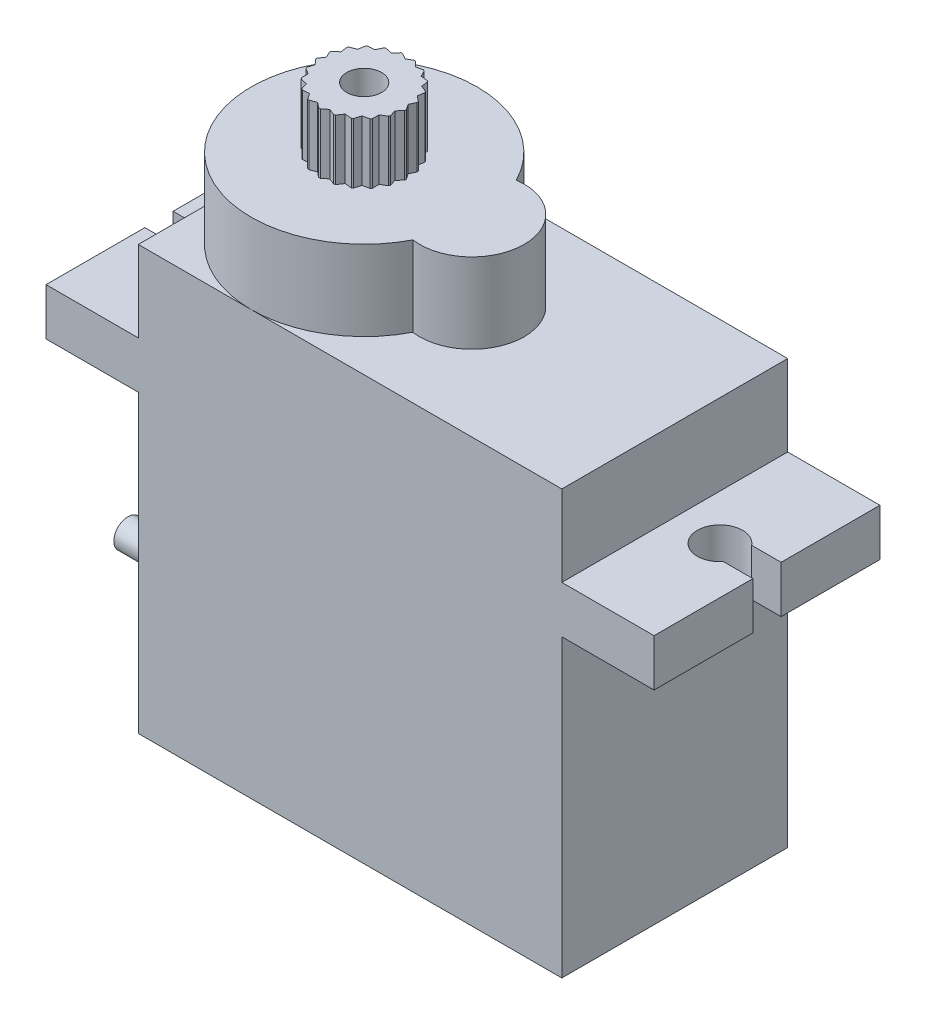
SolidWorks part; units mm, degrees
ref_plane "Front Plane" through (0, 0, 0) normal (0, 0, 1) x (1, 0, 0)
ref_plane "Top Plane" through (0, 0, 0) normal (0, 1, 0) x (1, 0, 0)
ref_plane "Right Plane" through (0, 0, 0) normal (1, 0, 0) x (0, 0, -1)
sketch "Sketch1" plane through (0, 0, 0) normal (0, 1, 0) x (1, 0, 0)
  line L1 (-11.25, -6) -> (11.25, -6)
  line L2 (-11.25, -6) -> (-11.25, 6)
  line L3 (-11.25, 6) -> (11.25, 6)
  line L4 (11.25, -6) -> (11.25, 6)
  line L5 (-11.25, -6) -> (11.25, 6) construction
  line L6 (-11.25, 6) -> (11.25, -6) construction
  point P0 (0, 0)
  dimension "D1" = 22.5
  dimension "D2" = 12
extrude "Boss-Extrude1" add sketch "Sketch1" along normal mid plane 22.5
sketch "Sketch3" plane through (0, 11.25, 0) normal (0, 1, 0) x (1, 0, 0)
  line L0 (-12.375, 0) -> (12.375, 0) construction
  line L1 (11.25, 6) -> (-11.25, 6) construction
  line L2 (-11.25, 6) -> (-11.25, -6) construction
  circle A0 centre (-5.25, 0) radius 6
  circle A1 centre (0.4725, 0) radius 2.7775
  point P10 (3.25, 0)
  point P11 (0.0827, -2.75)
  point P13 (0.0827, 2.75)
  dimension "D1" = 5.5
  dimension "D2" = 14.5
extrude "Boss-Extrude3" add sketch "Sketch3" along normal blind 4.25 contours A0 A1 | A0 A1 | A1 A0
ref_plane "Plane1" through (0, 6.95, 0) normal (0, 1, 0) x (1, 0, 0)
sketch "Sketch4" plane through (0, 6.95, 0) normal (0, 1, 0) x (1, 0, 0)
  line L0 (-5.25, -6) -> (11.25, -6) construction
  line L1 (11.25, 6) -> (16.15, 6)
  line L2 (11.25, 6) -> (11.25, -6)
  line L3 (11.25, -6) -> (16.15, -6)
  line L4 (16.15, 6) -> (16.15, -6)
  dimension "D1" = 4.9
extrude "Boss-Extrude4" add sketch "Sketch4" against normal blind 2.5
sketch "Sketch5" plane through (0, 6.95, 0) normal (0, 1, 0) x (1, 0, 0)
  line L0 (16.15, -6) -> (16.15, 6) construction
  line L1 (16.15, 0.75) -> (14.5867, 0.75)
  line L2 (16.15, -0.75) -> (14.5867, -0.75)
  line L3 (16.15, 0.75) -> (16.15, -0.75)
  line L4 (16.15, 0.75) -> (16.15, -0.75)
  circle A0 centre (13.65, 0) radius 1.2
  point P8 (16.15, 0)
  point P9 (16.15, 0)
  line M7 (16.15, -6) -> (16.15, 6)
  dimension "D2" = 2.4
  dimension "D1" = 2.5
  dimension "D3" = 1.5
extrude "Cut-Extrude1" cut sketch "Sketch5" against normal up to surface (2.5 mm away) contours A0 L2 L1 M7 | A0 up to face at (13.7, 4.45, 0)
mirror "Mirror1" about plane through (0, 0, 0) normal (1, 0, 0) of "Cut-Extrude1", "Boss-Extrude4"
sketch "Sketch6" plane through (-11.25, 0, 0) normal (-1, 0, 0) x (0, 0, 1)
  line L0 (-6, -11.25) -> (6, -11.25) construction
  circle A0 centre (0, -6.75) radius 0.75
  circle A1 centre (1.55, -6.75) radius 0.75
  circle A2 centre (-1.55, -6.75) radius 0.75
  dimension "D1" = 1.5
  dimension "D2" = 1.5
  dimension "D3" = 1.5
  dimension "D4" = 1.55
  dimension "D5" = 1.55
  dimension "D6" = 4.5
extrude "Boss-Extrude5" add sketch "Sketch6" along normal blind 5
sketch "Sketch7" plane through (0, 15.5, 0) normal (0, 1, 0) x (1, 0, 0)
  circle A0 centre (-5.25, 0) radius 2.375
  dimension "D1" = 4.75
extrude "Boss-Extrude6" add sketch "Sketch7" along normal blind 3.2
sketch "Sketch8" plane through (0, 18.7, 0) normal (0, 1, 0) x (1, 0, 0)
  line L0 (-5.25, 2.375) -> (-5.25, 2.175)
  line L1 (-5.25, 2.175) -> (-4.939, 2.3546)
  line L2 (-5.25, 2.175) -> (-5.561, 2.3546)
  line L3 (-4.6089, 2.0784) -> (-4.2588, 2.1583)
  line L4 (-4.55, 2.2695) -> (-4.6089, 2.0784)
  line L5 (-4.6089, 2.0784) -> (-4.8532, 2.3416)
  line L6 (-4.0248, 1.7971) -> (-3.6667, 1.7702)
  line L7 (-3.9121, 1.9623) -> (-4.0248, 1.7971)
  line L8 (-4.0248, 1.7971) -> (-4.1806, 2.1206)
  line L9 (-3.5495, 1.3561) -> (-3.2152, 1.2249)
  line L10 (-3.3932, 1.4808) -> (-3.5495, 1.3561)
  line L11 (-3.5495, 1.3561) -> (-3.603, 1.7112)
  line L12 (-3.2253, 0.7946) -> (-2.9446, 0.5707)
  line L13 (-3.0392, 0.8677) -> (-3.2253, 0.7946)
  line L14 (-3.2253, 0.7946) -> (-3.1718, 1.1497)
  line L15 (-3.0811, 0.1625) -> (-2.8788, -0.1342)
  line L16 (-2.8816, 0.1775) -> (-3.0811, 0.1625)
  line L17 (-3.0811, 0.1625) -> (-2.9253, 0.4861)
  line L18 (-3.1295, -0.484) -> (-3.0237, -0.8271)
  line L19 (-2.9345, -0.5285) -> (-3.1295, -0.484)
  line L20 (-3.1295, -0.484) -> (-2.8853, -0.2207)
  line L21 (-3.3664, -1.0875) -> (-3.3664, -1.4466)
  line L22 (-3.1932, -1.1875) -> (-3.3664, -1.0875)
  line L23 (-3.3664, -1.0875) -> (-3.0554, -0.9079)
  line L24 (-3.7706, -1.5944) -> (-3.8765, -1.9375)
  line L25 (-3.6346, -1.741) -> (-3.7706, -1.5944)
  line L26 (-3.7706, -1.5944) -> (-3.4205, -1.5145)
  line L27 (-4.3063, -1.9596) -> (-4.5086, -2.2563)
  line L28 (-4.2195, -2.1398) -> (-4.3063, -1.9596)
  line L29 (-4.3063, -1.9596) -> (-3.9482, -1.9864)
  line L30 (-4.9258, -2.1507) -> (-5.2066, -2.3746)
  line L31 (-4.896, -2.3485) -> (-4.9258, -2.1507)
  line L32 (-4.9258, -2.1507) -> (-4.5916, -2.2819)
  line L33 (-5.5742, -2.1507) -> (-5.9084, -2.2819)
  line L34 (-5.604, -2.3485) -> (-5.5742, -2.1507)
  line L35 (-5.5742, -2.1507) -> (-5.2934, -2.3746)
  line L36 (-6.1937, -1.9596) -> (-6.5518, -1.9864)
  line L37 (-6.2805, -2.1398) -> (-6.1937, -1.9596)
  line L38 (-6.1937, -1.9596) -> (-5.9914, -2.2563)
  line L39 (-6.7294, -1.5944) -> (-7.0795, -1.5145)
  line L40 (-6.8654, -1.741) -> (-6.7294, -1.5944)
  line L41 (-6.7294, -1.5944) -> (-6.6235, -1.9375)
  line L42 (-7.1336, -1.0875) -> (-7.4446, -0.9079)
  line L43 (-7.3068, -1.1875) -> (-7.1336, -1.0875)
  line L44 (-7.1336, -1.0875) -> (-7.1336, -1.4466)
  line L45 (-7.3705, -0.484) -> (-7.6147, -0.2207)
  line L46 (-7.5655, -0.5285) -> (-7.3705, -0.484)
  line L47 (-7.3705, -0.484) -> (-7.4763, -0.8271)
  line L48 (-7.4189, 0.1625) -> (-7.5747, 0.4861)
  line L49 (-7.6184, 0.1775) -> (-7.4189, 0.1625)
  line L50 (-7.4189, 0.1625) -> (-7.6212, -0.1342)
  line L51 (-7.2747, 0.7946) -> (-7.3282, 1.1497)
  line L52 (-7.4608, 0.8677) -> (-7.2747, 0.7946)
  line L53 (-7.2747, 0.7946) -> (-7.5554, 0.5707)
  line L54 (-6.9505, 1.3561) -> (-6.897, 1.7112)
  line L55 (-7.1068, 1.4808) -> (-6.9505, 1.3561)
  line L56 (-6.9505, 1.3561) -> (-7.2848, 1.2249)
  line L57 (-6.4752, 1.7971) -> (-6.3194, 2.1206)
  line L58 (-6.5879, 1.9623) -> (-6.4752, 1.7971)
  line L59 (-6.4752, 1.7971) -> (-6.8333, 1.7702)
  line L60 (-5.8911, 2.0784) -> (-5.6468, 2.3416)
  line L61 (-5.95, 2.2695) -> (-5.8911, 2.0784)
  line L62 (-5.8911, 2.0784) -> (-6.2412, 2.1583)
  circle A0 centre (-5.25, 0) radius 2.375 construction
  circle A1 centre (-5.25, 0) radius 2.375 construction
  arc A2 (-5.561, 2.3546) -> (-4.939, 2.3546) centre (-5.25, 0) cw
  arc A3 (-4.8532, 2.3416) -> (-4.2588, 2.1583) centre (-5.25, 0) cw
  arc A4 (-4.1806, 2.1206) -> (-3.6667, 1.7702) centre (-5.25, 0) cw
  arc A5 (-3.603, 1.7112) -> (-3.2152, 1.2249) centre (-5.25, 0) cw
  arc A6 (-3.1718, 1.1497) -> (-2.9446, 0.5707) centre (-5.25, 0) cw
  arc A7 (-2.9253, 0.4861) -> (-2.8788, -0.1342) centre (-5.25, 0) cw
  arc A8 (-2.8853, -0.2207) -> (-3.0237, -0.8271) centre (-5.25, 0) cw
  arc A9 (-3.0554, -0.9079) -> (-3.3664, -1.4466) centre (-5.25, 0) cw
  arc A10 (-3.4205, -1.5145) -> (-3.8765, -1.9375) centre (-5.25, 0) cw
  arc A11 (-3.9482, -1.9864) -> (-4.5086, -2.2563) centre (-5.25, 0) cw
  arc A12 (-4.5916, -2.2819) -> (-5.2066, -2.3746) centre (-5.25, 0) cw
  arc A13 (-5.2934, -2.3746) -> (-5.9084, -2.2819) centre (-5.25, 0) cw
  arc A14 (-5.9914, -2.2563) -> (-6.5518, -1.9864) centre (-5.25, 0) cw
  arc A15 (-6.6235, -1.9375) -> (-7.0795, -1.5145) centre (-5.25, 0) cw
  arc A16 (-7.1336, -1.4466) -> (-7.4446, -0.9079) centre (-5.25, 0) cw
  arc A17 (-7.4763, -0.8271) -> (-7.6147, -0.2207) centre (-5.25, 0) cw
  arc A18 (-7.6212, -0.1342) -> (-7.5747, 0.4861) centre (-5.25, 0) cw
  arc A19 (-7.5554, 0.5707) -> (-7.3282, 1.1497) centre (-5.25, 0) cw
  arc A20 (-7.2848, 1.2249) -> (-6.897, 1.7112) centre (-5.25, 0) cw
  arc A21 (-6.8333, 1.7702) -> (-6.3194, 2.1206) centre (-5.25, 0) cw
  arc A22 (-6.2412, 2.1583) -> (-5.6468, 2.3416) centre (-5.25, 0) cw
  point P92 (-5.25, 0)
  circle M4 centre (-5.25, 0) radius 2.375
  dimension "D1" = 60
  dimension "D2" = 60
  dimension "D3" = 0.2
  dimension "D4" = 21
extrude "Cut-Extrude2" cut sketch "Sketch8" against normal up to surface (3.2 mm away) contours L0 L1 M4 | L2 L0 M4 | L5 L4 M4 | L4 L3 M4 | L8 L7 M4 | L7 L6 M4 | L11 L10 M4 | L14 L13 M4 | L13 L12 M4 | L58 L57 M4 | L59 L58 M4 | L55 L54 M4 | L56 L55 M4 | L17 L16 M4 | L16 L15 M4 | L20 L19 M4 | L19 L18 M4 | L23 L22 M4 | L22 L21 M4 | L26 L25 M4 | L25 L24 M4 | L29 L28 M4 | L28 L27 M4 | L32 L31 M4 | L31 L30 M4 | L35 L34 M4 | L34 L33 M4 | L38 L37 M4 | L37 L36 M4 | L41 L40 M4 | L40 L39 M4 | L43 L42 M4 | L44 L43 M4 | L53 L52 M4 | L52 L51 M4 | L49 L48 M4 | L50 L49 M4 | L46 L45 M4 | L47 L46 M4 | L62 A22 L60
sketch "Sketch9" plane through (0, 18.7, 0) normal (0, 1, 0) x (1, 0, 0)
  circle A0 centre (-5.25, 0) radius 0.925
  dimension "D1" = 1.85
extrude "Cut-Extrude3" cut sketch "Sketch9" against normal up to surface (3.2 mm away) up to face at (-5.25, 15.5, 0)
